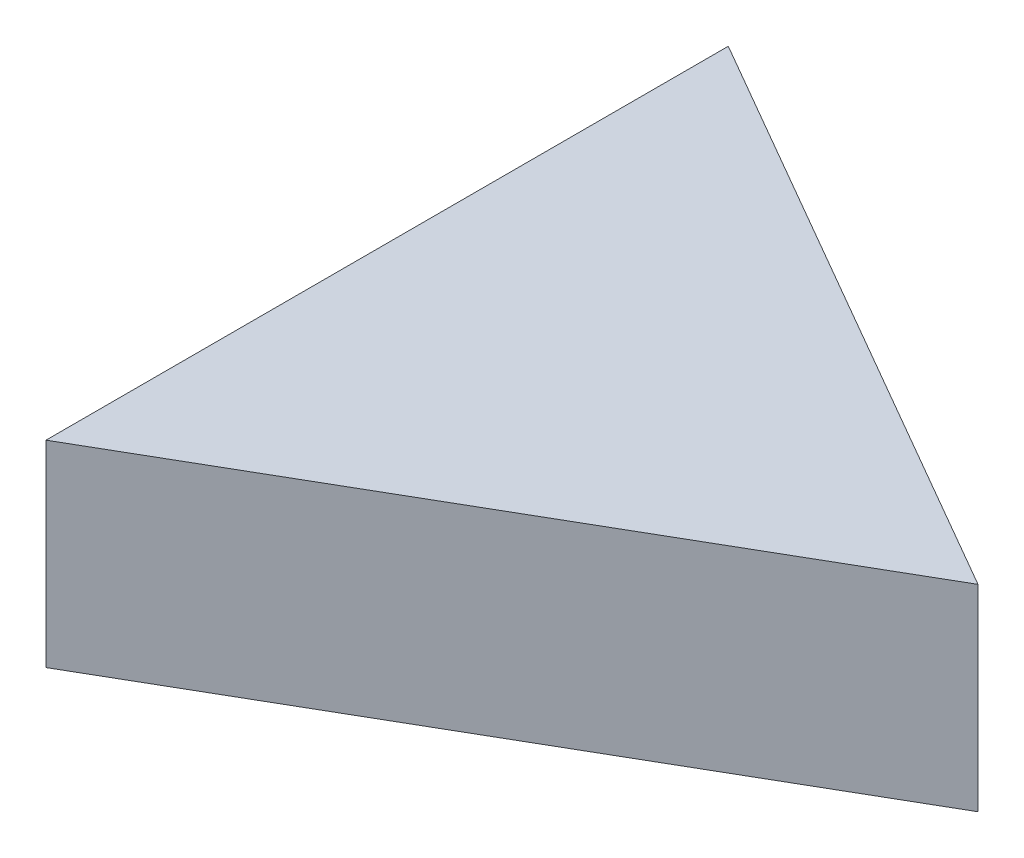
SolidWorks part; units mm, degrees
ref_plane "Front Plane" through (0, 0, 0) normal (0, 0, 1) x (1, 0, 0)
ref_plane "Top Plane" through (0, 0, 0) normal (0, 1, 0) x (1, 0, 0)
ref_plane "Right Plane" through (0, 0, 0) normal (1, 0, 0) x (0, 0, -1)
sketch "Sketch1" plane through (0, 0, 0) normal (0, 1, 0) x (1, 0, 0)
  line L1 (40, 0) -> (-20, 34.641)
  line L2 (-20, 34.641) -> (-20, -34.641)
  line L3 (-20, -34.641) -> (40, 0)
  circle A0 centre (0, 0) radius 40 construction
extrude "Boss-Extrude1" add sketch "Sketch1" along normal blind 20
